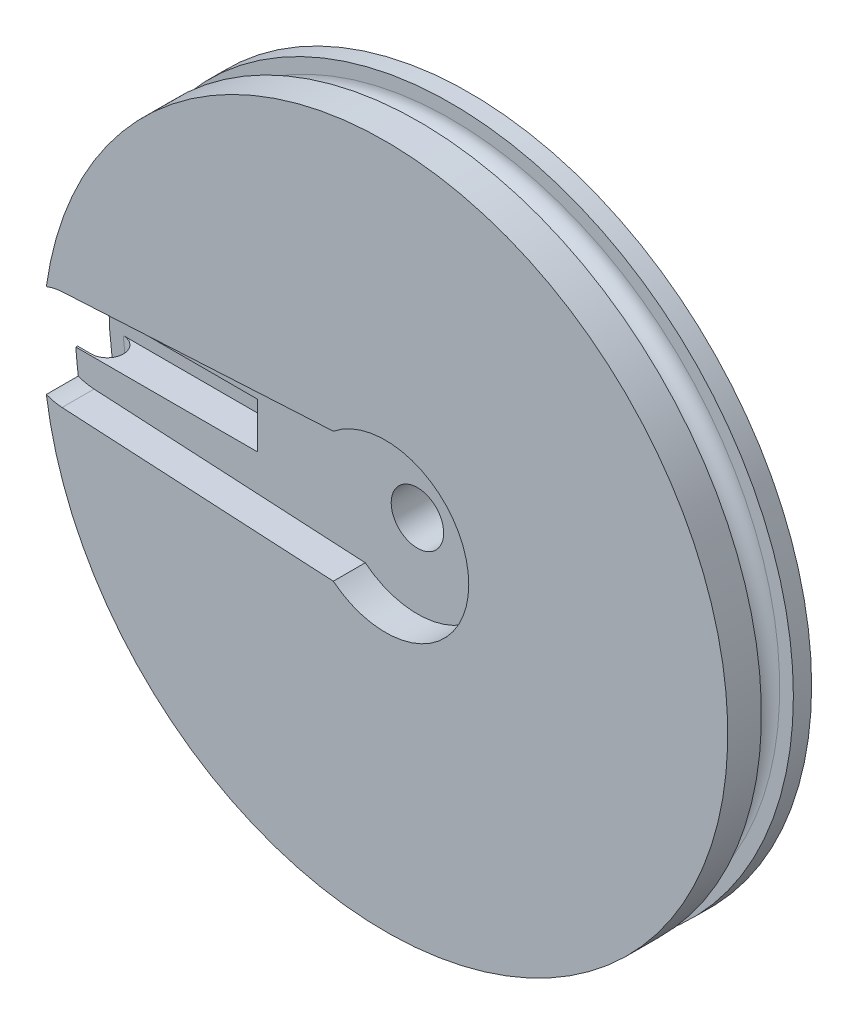
SolidWorks part; units mm, degrees
ref_plane "Front Plane" through (0, 0, 0) normal (0, 0, 1) x (1, 0, 0)
ref_plane "Top Plane" through (0, 0, 0) normal (0, 1, 0) x (1, 0, 0)
ref_plane "Right Plane" through (0, 0, 0) normal (1, 0, 0) x (0, 0, -1)
sketch "Sketch1" plane through (0, 0, 0) normal (1, 0, 0) x (0, 0, -1)
  line L1 (-1.8375, 0) -> (1.8375, 0)
  line L2 (-1.8375, 0) -> (-1.8375, 15)
  line L4 (1.8375, 0) -> (1.8375, 15)
  line L5 (-1.8375, 15) -> (-0.3625, 15)
  line L6 (-0.3625, 15) -> (-0.3625, 14.4)
  line L7 (1.0375, 14.4) -> (1.0375, 15)
  line L8 (1.0375, 15) -> (1.8375, 15)
  arc A0 (-0.3625, 14.4) -> (1.0375, 14.4) centre (0.3375, 14.4) ccw
  dimension "D2" = 0.7
  dimension "D1" = 15
  dimension "D3" = 0.6
  dimension "D4" = 0.8
  dimension "D5" = 2.175
revolve "Revolve1" add sketch "Sketch1" angle 360 about L1
sketch "Sketch2" plane through (0, 0, 1.8375) normal (0, 0, 1) x (1, 0, 0)
  line L0 (-2.2852, 2.8461) -> (-14.17, 2.1967)
  line L1 (-14.17, -2.1967) -> (-2.2852, -2.8461)
  line L4 (-2.2091, 2.65) -> (-14.1591, 1.997) construction
  line L5 (-14.1591, -1.997) -> (-2.2091, -2.65) construction
  arc A0 (-14.17, 2.1967) -> (-14.17, -2.1967) centre (-14.05, 0) ccw
  arc A1 (-2.2852, -2.8461) -> (-2.2852, 2.8461) centre (0, 0) ccw
  arc A4 (-2.2091, -2.65) -> (-2.2091, 2.65) centre (0, 0) ccw construction
  arc A5 (-14.1591, 1.997) -> (-14.1591, -1.997) centre (-14.05, 0) ccw construction
  circle A6 centre (-4.45, 0) radius 0.6 construction
  circle A8 centre (0, 0) radius 2.3 construction
  circle A10 centre (-10.45, 0) radius 0.6 construction
  circle A12 centre (-8.45, 0) radius 0.6 construction
  circle A14 centre (-6.45, 0) radius 0.6 construction
  circle A16 centre (-14.45, 0) radius 0.6 construction
  circle A18 centre (-12.45, 0) radius 0.6 construction
  dimension "D1" = 0.2
extrude "Cut-Extrude1" cut sketch "Sketch2" against normal blind 1.4 contours L0 A0 L1 A1
sketch "Sketch3" plane through (0, 0, 1.8375) normal (0, 0, 1) x (1, 0, 0)
  line L0 (3.65, 0) -> (-18.8, 0) construction
  line L3 (-2.2852, -2.8461) -> (-14.17, -2.1967)
  line L4 (-2.2852, -2.8461) -> (-14.17, -2.1967)
  line L5 (-14.17, 2.1967) -> (-2.2852, 2.8461)
  line L6 (-14.17, 2.1967) -> (-2.2852, 2.8461)
  arc A0 (-2.2852, -2.8461) -> (-2.2852, 2.8461) centre (0, 0) ccw construction
  arc A1 (-14.8599, -2.0455) -> (-14.17, -2.1967) centre (-14.05, 0) ccw
  arc A7 (-14.8599, -2.0455) -> (-14.17, -2.1967) centre (-14.05, 0) ccw
  arc A9 (-14.8599, -2.0455) -> (-14.8599, 2.0455) centre (0, 0) ccw
  arc A10 (-14.8599, -2.0455) -> (-14.8599, 2.0455) centre (0, 0) ccw
  arc A13 (-14.17, 2.1967) -> (-14.8599, 2.0455) centre (-14.05, 0) ccw
  arc A16 (-14.17, 2.1967) -> (-14.8599, 2.0455) centre (-14.05, 0) ccw
  arc A18 (-2.2852, -2.8461) -> (-2.2852, 2.8461) centre (0, 0) ccw
  arc A19 (-2.2852, -2.8461) -> (-2.2852, 2.8461) centre (0, 0) ccw
  dimension "D1" = 0
sketch "Sketch5" plane through (0, 0, -1.8375) normal (0, 0, -1) x (-1, 0, 0)
  circle A0 centre (0, 0) radius 1.15
  dimension "D1" = 2.3
extrude "Cut-Extrude2" cut sketch "Sketch5" against normal through all
sketch "Sketch6" plane through (0, 0, 0.4375) normal (0, 0, 1) x (1, 0, 0)
  line L0 (-7, -1) -> (-7, 1)
  line L1 (-15, 1) -> (-7, 1)
  line L2 (-15, 1) -> (-15, -1)
  line L3 (-15, -1) -> (-7, -1)
  arc A0 (-14.8599, 2.0455) -> (-14.8599, -2.0455) centre (0, 0) ccw construction
  arc A1 (-14.8599, 2.0455) -> (-14.8599, -2.0455) centre (0, 0) ccw
  point P3 (-7, 0)
  point P4 (-7.0099, 0.5565)
  arc M6 (-14.8599, 2.0455) -> (-14.8599, -2.0455) centre (0, 0) ccw
  dimension "D1" = 8
  dimension "D2" = 2
extrude "Cut-Extrude3" cut sketch "Sketch6" against normal up to surface (1.475 mm away) contours L3 L0 L1 M6 up to face at (14.4, 0, -1.0375)
